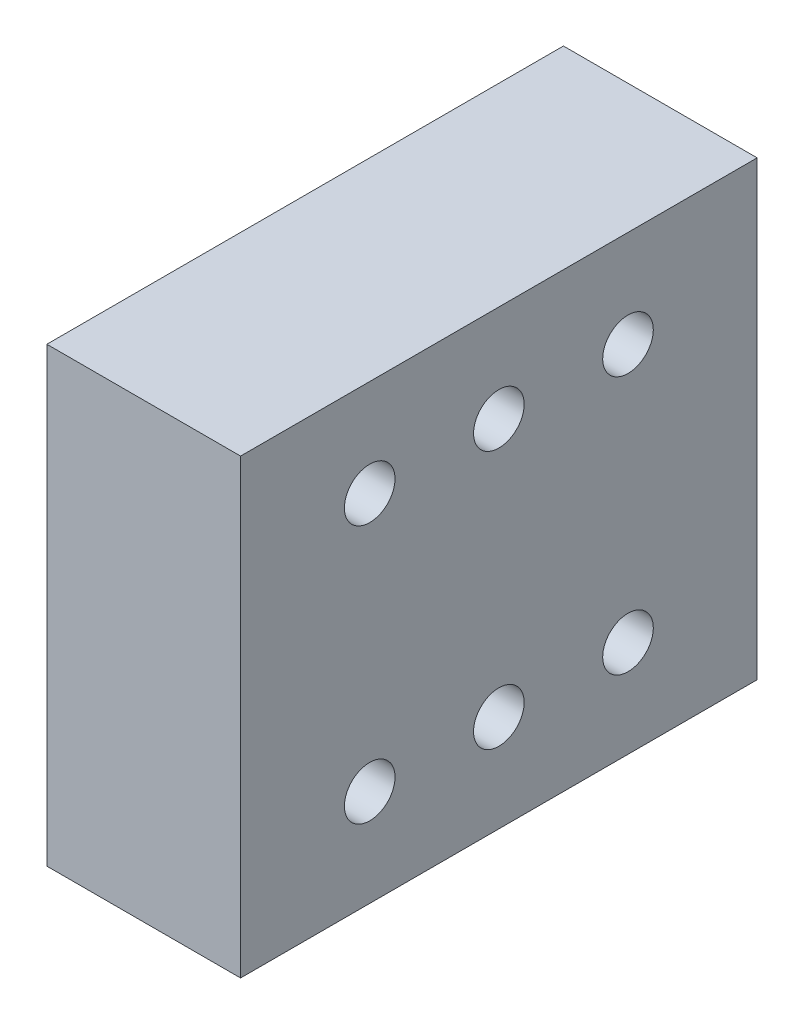
SolidWorks part; units mm, degrees
ref_plane "Front Plane" through (0, 0, 0) normal (0, 0, 1) x (1, 0, 0)
ref_plane "Top Plane" through (0, 0, 0) normal (0, 1, 0) x (1, 0, 0)
ref_plane "Right Plane" through (0, 0, 0) normal (1, 0, 0) x (0, 0, -1)
sketch "Sketch1" plane through (0, 0, 0) normal (0, 0, 1) x (1, 0, 0)
  line L1 (0, 0) -> (19.05, 0)
  line L2 (0, 0) -> (0, 44.45)
  line L3 (0, 44.45) -> (19.05, 44.45)
  line L4 (19.05, 0) -> (19.05, 44.45)
  dimension "D1" = 44.45
  dimension "D2" = 19.05
extrude "Boss-Extrude1" add sketch "Sketch1" along normal blind 50.8
sketch "Sketch2" plane through (19.05, 0, 0) normal (1, 0, 0) x (0, 0, -1)
  line L0 (-50.8, 0) -> (0, 0) construction
  line L1 (-50.8, 0) -> (-50.8, 44.45) construction
  circle A0 centre (-38.1, 9.525) radius 2.4892
  circle A1 centre (-25.4, 9.525) radius 2.4892
  circle A2 centre (-12.7, 9.525) radius 2.4892
  circle A3 centre (-38.1, 34.925) radius 2.4892
  circle A4 centre (-25.4, 34.925) radius 2.4892
  circle A5 centre (-12.7, 34.925) radius 2.4892
  dimension "D1" = 4.9784
  dimension "D2" = 9.525
  dimension "D3" = 12.7
  dimension "D4" = 3
  dimension "D5" = 2
extrude "Cut-Extrude1" cut sketch "Sketch2" against normal through all
